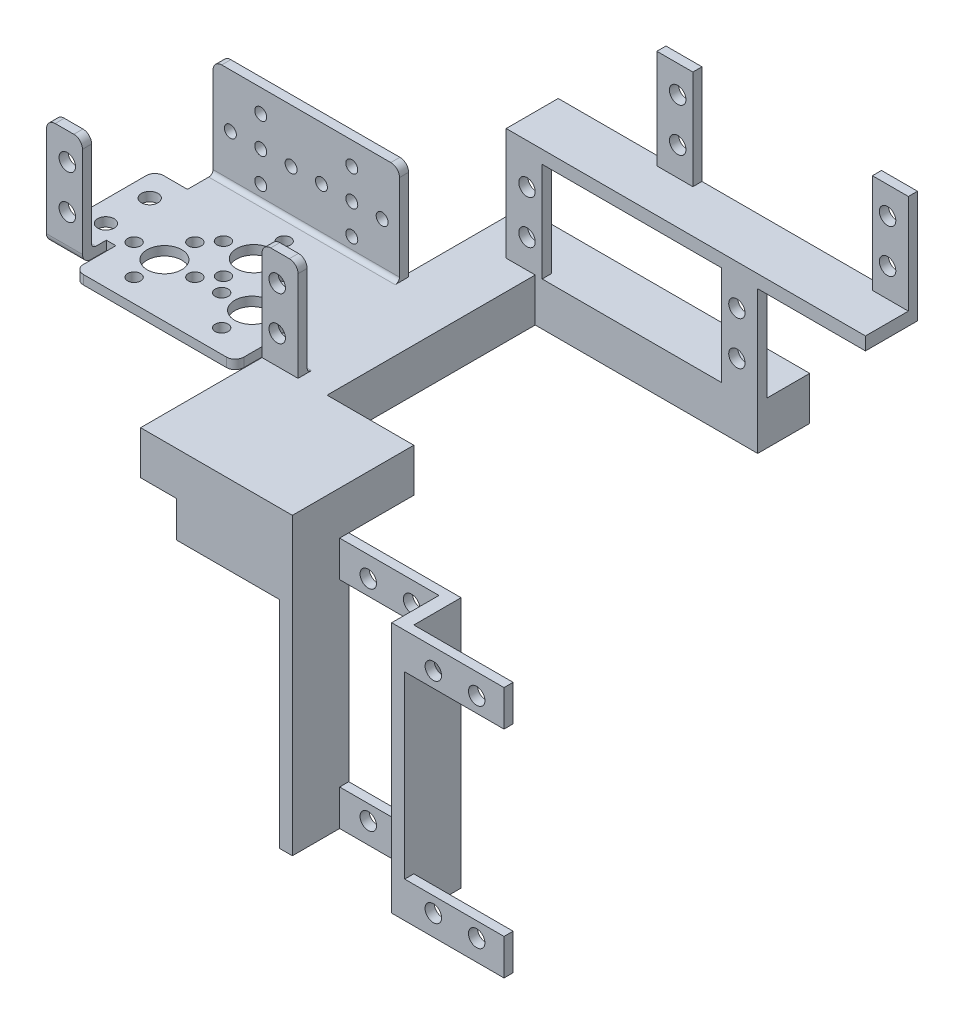
SolidWorks part; units mm, degrees
ref_plane "Front Plane" through (0, 0, 0) normal (0, 0, 1) x (1, 0, 0)
ref_plane "Top Plane" through (0, 0, 0) normal (0, 1, 0) x (1, 0, 0)
ref_plane "Right Plane" through (0, 0, 0) normal (1, 0, 0) x (0, 0, -1)
sketch "Sketch1" plane through (0, 0, 0) normal (0, 0, 1) x (1, 0, 0)
  line L1 (-29, -12.5) -> (29, -12.5)
  line L2 (-29, -12.5) -> (-29, 12.5)
  line L3 (-29, 12.5) -> (29, 12.5)
  line L4 (29, -12.5) -> (29, 12.5)
  line L5 (-29, -12.5) -> (29, 12.5) construction
  line L6 (-29, 12.5) -> (29, -12.5) construction
  point P0 (0, 0)
  dimension "D1" = 58
  dimension "D2" = 25
extrude "Boss-Extrude1" add sketch "Sketch1" along normal blind 37
sketch "Sketch2" plane through (-29, 0, 0) normal (-1, 0, 0) x (0, 0, 1)
  line L0 (37, 12.5) -> (0, 12.5) construction
  line L1 (2.1, 12.5) -> (30.9, 12.5)
  line L2 (2.1, 12.5) -> (2.1, -10.4)
  line L3 (2.1, -10.4) -> (30.9, -10.4)
  line L4 (30.9, 12.5) -> (30.9, -10.4)
  line L5 (0, 12.5) -> (0, -12.5) construction
  line L6 (37, -12.5) -> (0, -12.5) construction
  line L7 (37, 12.5) -> (37, -12.5) construction
  dimension "D1" = 2.1
  dimension "D2" = 2.1
  dimension "D3" = 6.1
extrude "Cut-Extrude1" cut sketch "Sketch2" against normal through all
sketch "Sketch3" plane through (0, 0, 37) normal (0, 0, 1) x (1, 0, 0)
  line L0 (29, 12.5) -> (-29, 12.5) construction
  line L1 (-20.3, 12.5) -> (20.3, 12.5)
  line L2 (-20.3, 12.5) -> (-20.3, -10.4)
  line L3 (-20.3, -10.4) -> (20.3, -10.4)
  line L4 (20.3, 12.5) -> (20.3, -10.4)
  line L5 (-29, -12.5) -> (29, -12.5) construction
  line L6 (-29, 12.5) -> (-29, -12.5) construction
  line L7 (29, -12.5) -> (29, 12.5) construction
  dimension "D1" = 2.1
  dimension "D2" = 8.7
  dimension "D3" = 8.7
extrude "Cut-Extrude2" cut sketch "Sketch3" against normal up to next
sketch "Sketch4" plane through (0, -12.5, 0) normal (0, -1, 0) x (1, 0, 0)
  line L1 (-29, 0) -> (-21.5, 0)
  line L2 (-29, 0) -> (-29, 8)
  line L3 (-29, 8) -> (-21.5, 8)
  line L4 (-21.5, 0) -> (-21.5, 8)
  line L5 (29, 0) -> (21.5, 0)
  line L6 (29, 0) -> (29, 8)
  line L7 (29, 8) -> (21.5, 8)
  line L8 (21.5, 0) -> (21.5, 8)
  dimension "D1" = 8
  dimension "D2" = 7.5
  dimension "D3" = 7.5
  dimension "D4" = 8
extrude "Cut-Extrude3" cut sketch "Sketch4" against normal through all
sketch "Sketch7" plane through (0, -12.5, 0) normal (0, -1, 0) x (1, 0, 0)
  line L1 (-29, 37) -> (-18.5, 37)
  line L2 (-29, 37) -> (-29, 33)
  line L3 (-29, 33) -> (-20.7, 33)
  line L4 (-18.5, 37) -> (-18.5, 33)
  line L5 (29, 37) -> (18.5, 37)
  line L6 (29, 37) -> (29, 33)
  line L7 (29, 33) -> (20.7, 33)
  line L8 (18.5, 37) -> (18.5, 33)
  line L10 (-18.5, 33) -> (-18.5, 27.5)
  line L11 (-18.5, 27.5) -> (-20.7, 27.5)
  line L12 (-20.7, 33) -> (-20.7, 27.5)
  line L14 (18.5, 33) -> (18.5, 27.5)
  line L15 (18.5, 27.5) -> (20.7, 27.5)
  line L16 (20.7, 33) -> (20.7, 27.5)
  dimension "D1" = 10.5
  dimension "D2" = 10.5
  dimension "D3" = 4
  dimension "D4" = 4
  dimension "D5" = 2.2
  dimension "D6" = 2.2
  dimension "D7" = 9.5
  dimension "D8" = 9.5
extrude "Cut-Extrude4" cut sketch "Sketch7" against normal through all
sketch "Sketch8" plane through (0, -10.4, 0) normal (0, 1, 0) x (-1, 0, 0)
  line L0 (0, 38.8401) -> (0, -3.117) construction
  line L1 (18.5, 37) -> (-18.5, 37) construction
  line L5 (-29, 8) -> (-29, 30.9) construction
  line L7 (29, 8) -> (29, 30.9) construction
  line L8 (21.5, 8) -> (29, 8) construction
  circle A0 centre (0, 14.2) radius 4
  circle A1 centre (7, 14.2) radius 1.5
  circle A2 centre (-7, 14.2) radius 1.5
  circle A3 centre (0, 7.2) radius 1.5
  circle A4 centre (0, 21.2) radius 1.5
  circle A7 centre (10.1, 24.7) radius 4
  circle A8 centre (17.1, 24.7) radius 1.5
  circle A9 centre (3.1, 24.7) radius 1.5
  circle A10 centre (10.1, 17.7) radius 1.5
  circle A11 centre (10.1, 31.7) radius 1.5
  circle A12 centre (-10.1, 24.7) radius 4
  circle A13 centre (-3.1, 24.7) radius 1.5
  circle A14 centre (-17.1, 24.7) radius 1.5
  circle A15 centre (-10.1, 17.7) radius 1.5
  circle A16 centre (-10.1, 31.7) radius 1.5
  circle A17 centre (24.1, 24.2) radius 1.9
  circle A18 centre (24.1, 14.1) radius 1.9
  circle A19 centre (-24.1, 14.1) radius 1.9
  circle A20 centre (-24.1, 24.2) radius 1.9
  dimension "D1" = 8
  dimension "D2" = 3
  dimension "D11" = 3.8
  dimension "D3" = 7
  dimension "D4" = 7
  dimension "D5" = 7
  dimension "D6" = 7
  dimension "D7" = 22.8
  dimension "D8" = 20.2
  dimension "D9" = 10.1
  dimension "D10" = 12.3
  dimension "D12" = 4.9
  dimension "D13" = 4.9
  dimension "D14" = 10.1
  dimension "D15" = 6.1
  dimension "D16" = 7
  dimension "D17" = 7
  dimension "D18" = 7
  dimension "D19" = 7
extrude "Cut-Extrude5" cut sketch "Sketch8" against normal through all
sketch "Sketch9" plane through (0, 0, 33) normal (0, 0, 1) x (1, 0, 0)
  line L0 (-29, 12.5) -> (-20.7, 12.5) construction
  line L1 (-29, 12.5) -> (-29, -12.5) construction
  line L2 (29, 12.5) -> (29, -12.5) construction
  circle A0 centre (-24.2, 6.2) radius 1.9
  circle A1 centre (-24.2, -3.8) radius 1.9
  circle A2 centre (24.2, 6.2) radius 1.9
  circle A3 centre (24.2, -3.8) radius 1.9
  dimension "D1" = 3.8
  dimension "D2" = 10
  dimension "D3" = 6.3
  dimension "D4" = 4.8
  dimension "D5" = 4.8
extrude "Cut-Extrude6" cut sketch "Sketch9" against normal up to next
sketch "Sketch10" plane through (0, 0, 0) normal (0, 0, -1) x (-1, 0, 0)
  line L0 (-21.5, 12.5) -> (21.5, 12.5) construction
  line L1 (0, 14.0161) -> (0, -13.408) construction
  circle A0 centre (-17.5, 0.22) radius 1.375
  circle A1 centre (-10.5, 0.22) radius 1.375
  circle A2 centre (-3.5, 0.22) radius 1.375
  circle A3 centre (3.5, 0.22) radius 1.375
  circle A4 centre (10.5, 0.22) radius 1.375
  circle A5 centre (17.5, 0.22) radius 1.375
  circle A6 centre (-10.5, 7.22) radius 1.375
  circle A7 centre (10.5, 7.22) radius 1.375
  circle A8 centre (-10.5, -6.78) radius 1.375
  circle A9 centre (10.5, -6.78) radius 1.375
  dimension "D1" = 2.75
  dimension "D2" = 12.28
  dimension "D3" = 7
  dimension "D4" = 7
  dimension "D5" = 7
  dimension "D6" = 7
  dimension "D7" = 7
  dimension "D8" = 3.5
  dimension "D9" = 7
  dimension "D10" = 7
extrude "Cut-Extrude7" cut sketch "Sketch10" against normal up to next
fillet "Fillet1" radius 2 13 edges at (0, -12.5, 0) (24.85, -12.5, 33) (-24.85, -12.5, 33) (-29, -11.45, 8) (29, -11.45, 8) (18.5, -11.45, 37) (-18.5, -11.45, 37) (-29, 12.5, 31.95) (-20.7, 12.5, 31.95) (20.7, 12.5, 31.95) (29, 12.5, 31.95) (21.5, 12.5, 1.05) (-21.5, 12.5, 1.05)
fillet "Fillet2" radius 1 3 edges at (-24.85, -10.4, 30.9) (24.85, -10.4, 30.9) (0, -10.4, 2.1)
sketch "Sketch15" plane through (0, -10.4, 0) normal (0, 1, 0) x (1, 0, 0)
  line L0 (20.7, 27) -> (87, 27)
  line L2 (20.7, 27) -> (20.7, -61)
  line L3 (20.7, -61) -> (52.7, -61)
  line L5 (29, 15) -> (29, -33)
  line L6 (29, -33) -> (52.7, -33)
  line L7 (29, 15) -> (87, 15)
  line L8 (52.7, -33) -> (55.7, -33)
  line L9 (87, 15) -> (87, 27)
  line L11 (55.7, -33) -> (55.7, -61)
  line L12 (52.7, -61) -> (55.7, -61)
  dimension "D1" = 28
  dimension "D2" = 32
  dimension "D3" = 12
  dimension "D4" = 58
  dimension "D5" = 3
extrude "Boss-Extrude3" add sketch "Sketch15" against normal blind 10
ref_plane "Plane4" through (0, -20.4, 0) normal (0, 1, 0) x (1, 0, 0)
sketch "Sketch16" plane through (0, -20.4, 0) normal (0, 1, 0) x (1, 0, 0)
  line L0 (52.7, -48) -> (78.6, -48)
  line L1 (78.6, -48) -> (78.6, -50.1)
  line L2 (78.6, -50.1) -> (55.7, -50.1)
  line L3 (55.7, -50.1) -> (55.7, -61)
  line L5 (52.7, -61) -> (52.7, -48)
  line L6 (55.7, -61) -> (55.7, -33) construction
  line L7 (20.7, -61) -> (55.7, -61) construction
  line L8 (52.7, -61) -> (55.7, -61)
  dimension "D1" = 22.9
  dimension "D2" = 2.1
  dimension "D3" = 3
extrude "Boss-Extrude4" add sketch "Sketch16" against normal blind 58
sketch "Sketch17" plane through (0, 0, 50.1) normal (0, 0, 1) x (1, 0, 0)
  line L0 (78.6, -78.4) -> (78.6, -20.4) construction
  line L1 (78.6, -28.7) -> (55.7, -28.7)
  line L2 (78.6, -28.7) -> (78.6, -70.1)
  line L3 (78.6, -70.1) -> (55.7, -70.1)
  line L4 (55.7, -28.7) -> (55.7, -70.1)
  line L5 (55.7, -78.4) -> (55.7, -20.4) construction
  line L6 (55.7, -20.4) -> (78.6, -20.4) construction
  line L7 (55.7, -78.4) -> (78.6, -78.4) construction
  dimension "D1" = 8.3
  dimension "D2" = 8.3
extrude "Cut-Extrude8" cut sketch "Sketch17" against normal blind 10
sketch "Sketch18" plane through (0, 0, 50.1) normal (0, 0, 1) x (1, 0, 0)
  line L0 (55.7, -20.4) -> (78.6, -20.4) construction
  line L1 (78.6, -28.7) -> (78.6, -20.4) construction
  line L2 (55.7, -78.4) -> (78.6, -78.4) construction
  circle A0 centre (72.3, -25.2) radius 1.9
  circle A1 centre (62.3, -25.2) radius 1.9
  circle A2 centre (72.3, -73.6) radius 1.9
  circle A3 centre (62.3, -73.6) radius 1.9
  dimension "D1" = 3.8
  dimension "D4" = 3.8
  dimension "D2" = 4.8
  dimension "D3" = 6.3
  dimension "D5" = 10
  dimension "D6" = 4.8
sketch "Sketch19" plane through (0, -20.4, 0) normal (0, 1, 0) x (1, 0, 0)
  line L0 (78.6, -48) -> (78.6, -61)
  line L3 (81.6, -61) -> (104.5, -61)
  line L4 (104.5, -61) -> (104.5, -58.9)
  line L5 (104.5, -58.9) -> (81.6, -58.9)
  line L6 (78.6, -50.1) -> (78.6, -48) construction
  line L10 (78.6, -61) -> (81.6, -61)
  line L12 (78.6, -48) -> (81.6, -48)
  line L13 (81.6, -48) -> (81.6, -58.9)
  line L17 (20.7, -61) -> (55.7, -61) construction
  line L18 (78.6, -48) -> (55.7, -48) construction
  dimension "D1" = 22.9
  dimension "D2" = 3
  dimension "D3" = 2.1
extrude "Boss-Extrude5" add sketch "Sketch19" against normal blind 58
sketch "Sketch20" plane through (0, 0, 61) normal (0, 0, 1) x (1, 0, 0)
  line L0 (104.5, -78.4) -> (104.5, -20.4) construction
  line L1 (104.5, -28.7) -> (81.6, -28.7)
  line L2 (104.5, -28.7) -> (104.5, -70.1)
  line L3 (104.5, -70.1) -> (81.6, -70.1)
  line L4 (81.6, -28.7) -> (81.6, -70.1)
  line L5 (78.6, -78.4) -> (78.6, -20.4) construction
  line L6 (78.6, -28.7) -> (55.7, -28.7) construction
  line L7 (55.7, -70.1) -> (78.6, -70.1) construction
  dimension "D1" = 3
extrude "Cut-Extrude9" cut sketch "Sketch20" against normal up to next
extrude "Cut-Extrude10" cut sketch "Sketch18" against normal up to next
sketch "Sketch23" plane through (0, 0, 61) normal (0, 0, 1) x (1, 0, 0)
  line L1 (78.6, -20.4) -> (104.5, -20.4) construction
  line L2 (104.5, -28.7) -> (104.5, -20.4) construction
  line L3 (104.5, -78.4) -> (104.5, -70.1) construction
  line L4 (78.6, -78.4) -> (104.5, -78.4) construction
  circle A0 centre (98.2, -25.2) radius 1.9
  circle A1 centre (88.2, -25.2) radius 1.9
  circle A2 centre (88.2, -73.6) radius 1.9
  circle A3 centre (98.2, -73.6) radius 1.9
  dimension "D1" = 3.8
  dimension "D4" = 3.8
  dimension "D6" = 3.8
  dimension "D7" = 3.8
  dimension "D2" = 6.3
  dimension "D3" = 4.8
  dimension "D5" = 10
  dimension "D8" = 6.3
  dimension "D9" = 4.8
extrude "Cut-Extrude11" cut sketch "Sketch23" against normal up to next
sketch "Sketch24" plane through (0, 0, -15) normal (0, 0, 1) x (1, 0, 0)
  line L0 (87, 12.5) -> (87, -10.4)
  line L1 (29, -10.4) -> (37.3, -10.4)
  line L2 (29, -10.4) -> (29, 12.5)
  line L3 (29, 12.5) -> (37.3, 12.5)
  line L4 (37.3, -10.4) -> (37.3, 12.5)
  line L8 (29, -10.4) -> (87, -10.4) construction
  line L13 (78.7, -10.4) -> (87, -10.4)
  line L14 (78.7, -10.4) -> (78.7, 12.5)
  line L15 (78.7, 12.5) -> (87, 12.5)
  circle A0 centre (33.8, 6.2) radius 1.9
  circle A1 centre (33.8, -3.8) radius 1.9
  circle A2 centre (82.2, 6.2) radius 1.8829
  circle A5 centre (82.2, -3.8) radius 1.8829
  dimension "D6" = 3.8
  dimension "D7" = 6.3
  dimension "D1" = 8.3
  dimension "D2" = 22.9
  dimension "D5" = 41.4
  dimension "D8" = 4.8
  dimension "D9" = 3.5
  dimension "D12" = 10
extrude "Boss-Extrude6" add sketch "Sketch24" against normal blind 2.1
sketch "Sketch25" plane through (0, -20.4, 0) normal (0, -1, 0) x (1, 0, 0)
  line L0 (52.7, 48) -> (52.7, 61) construction
  line L1 (29, 61) -> (52.7, 61)
  line L2 (29, 61) -> (29, 48)
  line L3 (29, 48) -> (52.7, 48)
  line L4 (52.7, 61) -> (52.7, 48)
  line L6 (29, 33) -> (29, -15) construction
  dimension "D1" = 13
extrude "Boss-Extrude7" add sketch "Sketch25" along normal blind 8.3
sketch "Sketch26" plane through (29, 0, 0) normal (1, 0, 0) x (0, 0, -1)
  line L1 (-33, -10.4) -> (15, -10.4)
  line L2 (-33, -10.4) -> (-33, -20.4)
  line L3 (-33, -20.4) -> (15, -20.4)
  line L4 (15, -10.4) -> (15, -20.4)
extrude "Boss-Extrude8" add sketch "Sketch26" along normal blind 6.7
sketch "Sketch28" plane through (0, 0, -27) normal (0, 0, -1) x (-1, 0, 0)
  line L1 (-87, -10.4) -> (-136.7, -10.4)
  line L2 (-87, -10.4) -> (-87, 12.5)
  line L3 (-87, 12.5) -> (-136.7, 12.5)
  line L4 (-136.7, -10.4) -> (-136.7, 12.5)
  circle A0 centre (-140.2, 6.2) radius 1.9456
  circle A1 centre (-140.2, -3.8) radius 1.9456
extrude "Boss-Extrude9" [suppressed] add sketch "Sketch28" against normal blind 2.1
sketch "Sketch29" plane through (0, 0, -27) normal (0, 0, -1) x (-1, 0, 0)
  line L1 (-95.3, 12.5) -> (-87, 12.5)
  line L2 (-95.3, 12.5) -> (-95.3, -10.4)
  line L3 (-95.3, -10.4) -> (-87, -10.4)
  line L4 (-87, 12.5) -> (-87, -10.4)
  circle A2 centre (-91.8, 6.2) radius 1.8829
  circle A3 centre (-91.8, -3.8) radius 1.8829
  dimension "D1" = 8.3
extrude "Boss-Extrude10" [suppressed] add sketch "Sketch29" against normal blind 2.1
sketch "Sketch33" plane through (0, 0, -15) normal (0, 0, 1) x (1, 0, 0)
  line L0 (37.3, 12.5) -> (29, 12.5) construction
  line L1 (29, 12.5) -> (111.85, 12.5)
  line L2 (29, 12.5) -> (29, 15.5)
  line L4 (111.85, 12.5) -> (111.85, 15.5)
  line L5 (29, 15.5) -> (111.85, 15.5)
  line L14 (58, -1.2835) -> (58, 10.9666) construction
  line L15 (37.3, -10.4) -> (37.3, 12.5) construction
  dimension "D1" = 3
  dimension "D5" = 20.7
extrude "Boss-Extrude12" add sketch "Sketch33" against normal blind 12
sketch "Sketch36" plane through (0, 0, -27) normal (0, 0, -1) x (-1, 0, 0)
  line L1 (-111.85, 38.4) -> (-103.55, 38.4)
  line L2 (-111.85, 38.4) -> (-111.85, 15.5)
  line L3 (-111.85, 15.5) -> (-103.55, 15.5)
  line L4 (-103.55, 38.4) -> (-103.55, 15.5)
  line L5 (-62.15, 38.4) -> (-53.85, 38.4)
  line L6 (-62.15, 38.4) -> (-62.15, 15.5)
  line L7 (-62.15, 15.5) -> (-53.85, 15.5)
  line L8 (-53.85, 38.4) -> (-53.85, 15.5)
  circle A0 centre (-107.05, 32.1) radius 1.9
  circle A1 centre (-107.05, 22.1) radius 1.9
  circle A2 centre (-58.65, 32.1) radius 1.9
  circle A3 centre (-58.65, 22.1) radius 1.9
extrude "Boss-Extrude13" add sketch "Sketch36" against normal blind 2.1
